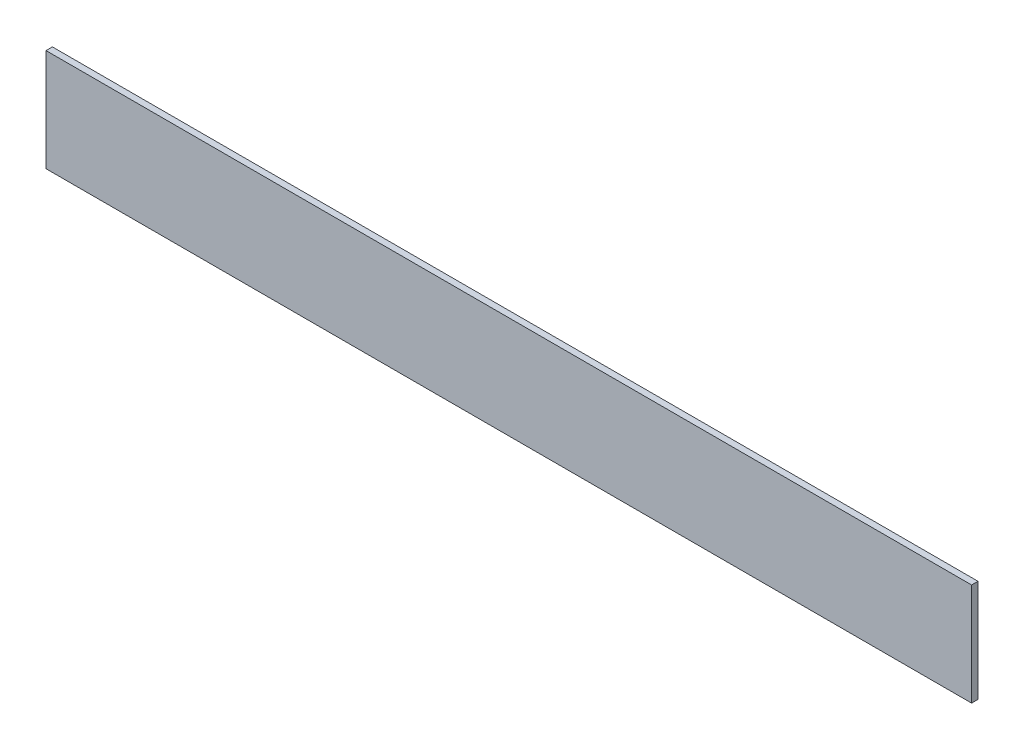
SolidWorks part; units mm, degrees
material "Custom Plastic"
ref_plane "X-Y Datum" through (0, 0, 0) normal (0, 0, 1) x (1, 0, 0)
ref_plane "X-Z Datum" through (0, 0, 0) normal (0, 1, 0) x (1, 0, 0)
ref_plane "Y-Z Datum" through (0, 0, 0) normal (1, 0, 0) x (0, 0, -1)
sketch "Sketch1" plane through (0, 0, 0) normal (0, 0, 1) x (1, 0, 0)
  line L1 (-229.745, 25.4) -> (229.745, 25.4)
  line L2 (-229.745, 25.4) -> (-229.745, -25.4)
  line L3 (-229.745, -25.4) -> (229.745, -25.4)
  line L4 (229.745, 25.4) -> (229.745, -25.4)
  line L5 (-229.745, 25.4) -> (229.745, -25.4) construction
  line L6 (-229.745, -25.4) -> (229.745, 25.4) construction
  point P0 (0, 0)
  dimension "D1" = 459.49
  dimension "D2" = 50.8
extrude "Boss-Extrude1" add sketch "Sketch1" along normal blind 3.175
